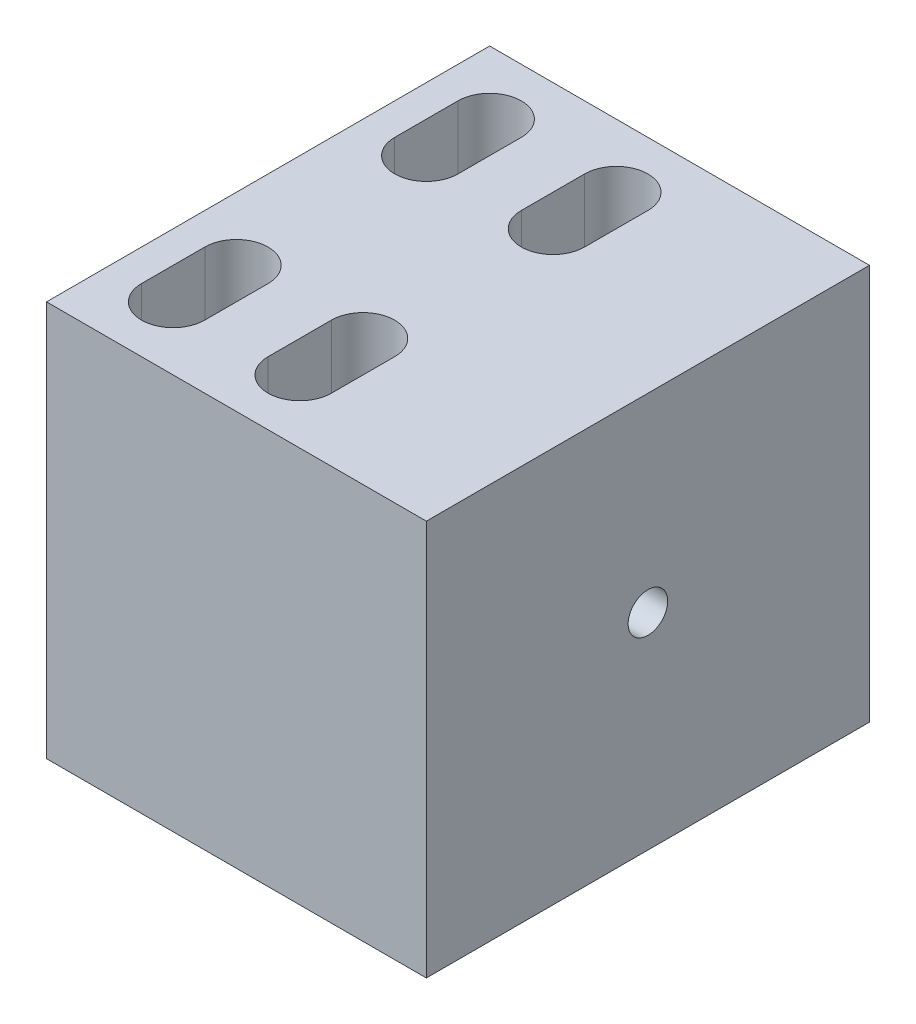
SolidWorks part; units mm, degrees
ref_plane "Front" through (0, 0, 0) normal (0, 0, 1) x (1, 0, 0)
ref_plane "Top" through (0, 0, 0) normal (0, 1, 0) x (1, 0, 0)
ref_plane "Right" through (0, 0, 0) normal (1, 0, 0) x (0, 0, -1)
sketch "Sketch1" plane through (0, 0, 0) normal (0, 1, 0) x (1, 0, 0)
  line L0 (4, 0) -> (4, 4)
  line L1 (0, 0) -> (24, 0)
  line L2 (0, 0) -> (0, 28)
  line L3 (0, 28) -> (24, 28)
  line L4 (24, 0) -> (24, 28)
  line L5 (4, 4) -> (4, 12)
  line L6 (4, 4) -> (4, 8) construction
  line L7 (2, 4) -> (2, 8)
  line L8 (6, 4) -> (6, 8)
  line L9 (12, 4) -> (12, 8) construction
  line L10 (10, 4) -> (10, 8)
  line L11 (14, 4) -> (14, 8)
  line L12 (12, 20) -> (12, 24) construction
  line L13 (10, 20) -> (10, 24)
  line L14 (14, 20) -> (14, 24)
  line L15 (4, 20) -> (4, 24) construction
  line L16 (2, 20) -> (2, 24)
  line L17 (6, 20) -> (6, 24)
  arc A0 (2, 4) -> (6, 4) centre (4, 4) ccw
  arc A1 (6, 8) -> (2, 8) centre (4, 8) ccw
  arc A2 (10, 4) -> (14, 4) centre (12, 4) ccw
  arc A3 (14, 8) -> (10, 8) centre (12, 8) ccw
  arc A4 (10, 20) -> (14, 20) centre (12, 20) ccw
  arc A5 (14, 24) -> (10, 24) centre (12, 24) ccw
  arc A6 (2, 20) -> (6, 20) centre (4, 20) ccw
  arc A7 (6, 24) -> (2, 24) centre (4, 24) ccw
  point P8 (4, 6)
  point P18 (12, 6)
  point P25 (12, 22)
  point P32 (4, 22)
  dimension "D7" = 2
  dimension "D1" = 24
  dimension "D2" = 28
  dimension "D3" = 4
  dimension "D4" = 4
  dimension "D5" = 8
  dimension "D6" = 4
  dimension "D8" = 2
  dimension "D9" = 2
extrude "Boss-Extrude1" add sketch "Sketch1" along normal blind 25
sketch "Sketch2" plane through (24, 0, 0) normal (1, 0, 0) x (0, 0, -1)
  line L0 (14, 25) -> (14, 13)
  line L1 (0, 25) -> (28, 25) construction
  circle A0 centre (14, 13) radius 1.25
  dimension "D1" = 12
extrude "Cut-Extrude1" cut sketch "Sketch2" against normal through all
